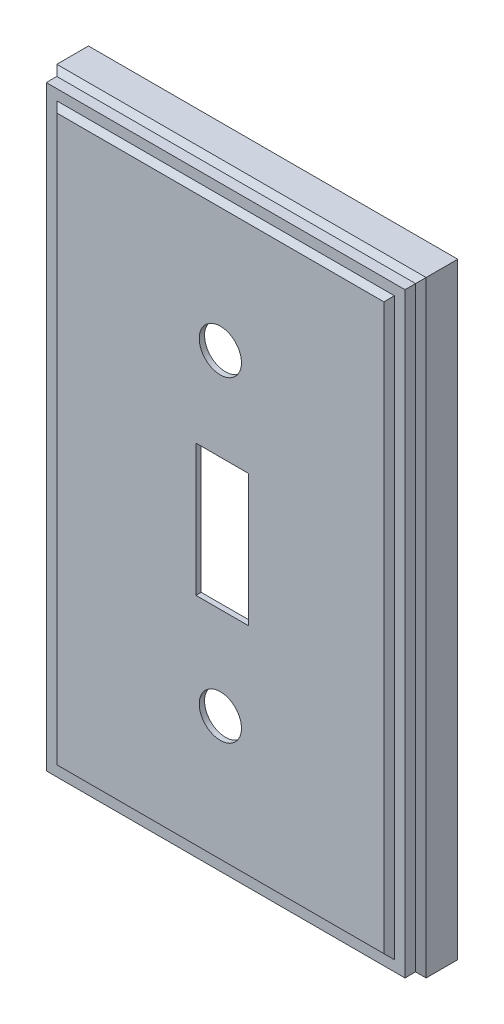
SolidWorks part; units mm, degrees
ref_plane "Front Plane" through (0, 0, 0) normal (0, 0, 1) x (1, 0, 0)
ref_plane "Top Plane" through (0, 0, 0) normal (0, 1, 0) x (1, 0, 0)
ref_plane "Right Plane" through (0, 0, 0) normal (1, 0, 0) x (0, 0, -1)
sketch "Sketch1" plane through (0, 0, 0) normal (0, 0, 1) x (1, 0, 0)
  line L1 (0, 0) -> (70, 0)
  line L2 (0, 0) -> (0, -115)
  line L3 (0, -115) -> (70, -115)
  line L4 (70, 0) -> (70, -115)
  dimension "D1" = 70
  dimension "D2" = 115
extrude "Boss-Extrude1" add sketch "Sketch1" along normal blind 10
shell "Shell2" thickness 1
sketch "Sketch2" plane through (0, 0, 10) normal (0, 0, 1) x (1, 0, 0)
  line L0 (0, -115) -> (70, -115) construction
  line L1 (0, 0) -> (0, -115) construction
  line L3 (30.3697, -45) -> (40.3697, -45)
  line L4 (30.3697, -45) -> (30.3697, -70)
  line L5 (30.3697, -70) -> (40.3697, -70)
  line L6 (40.3697, -45) -> (40.3697, -70)
  circle A0 centre (35, -27.5) radius 4
  circle A1 centre (35, -87.5) radius 4
  point P12 (35.3697, -70)
  dimension "D1" = 8
  dimension "D2" = 8
  dimension "D3" = 60
  dimension "D4" = 27.5
  dimension "D5" = 35
  dimension "D6" = 10
  dimension "D7" = 25
  dimension "D8" = 45
extrude "Cut-Extrude1" cut sketch "Sketch2" against normal up to surface (10 mm away) up to face at (35, -57.5, 0)
chamfer "Chamfer1" distance 4 angle 45 4 edges at (35, -115, 10) (0, -57.5, 10) (35, 0, 10) (70, -57.5, 10)
